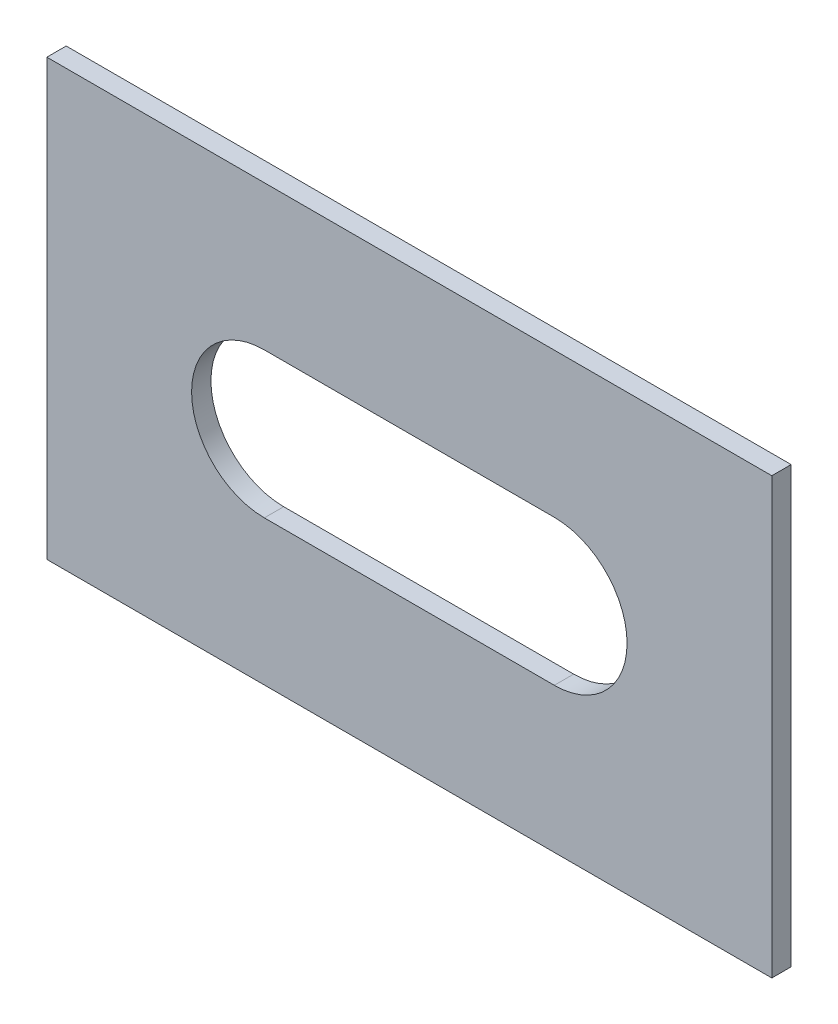
SolidWorks part; units mm, degrees
ref_plane "Front" through (0, 0, 0) normal (0, 0, 1) x (1, 0, 0)
ref_plane "Top" through (0, 0, 0) normal (0, 1, 0) x (1, 0, 0)
ref_plane "Right" through (0, 0, 0) normal (1, 0, 0) x (0, 0, -1)
sketch "Sketch1" plane through (0, 0, 0) normal (0, 0, 1) x (1, 0, 0)
  line L0 (29.95, 29.95) -> (45, 29.95) construction
  line L1 (0, 0) -> (150, 0)
  line L2 (0, 0) -> (0, 90)
  line L3 (0, 90) -> (150, 90)
  line L4 (150, 0) -> (150, 90)
  line L5 (45, 29.95) -> (105, 29.95)
  line L6 (45, 60.05) -> (105, 60.05)
  line L7 (29.95, 29.95) -> (29.95, 45) construction
  arc A6 (45, 60.05) -> (45, 29.95) centre (45, 45) ccw
  arc A7 (105, 29.95) -> (105, 60.05) centre (105, 45) ccw
  point P14 (120.05, 45)
  dimension "D3" = 30.1
  dimension "D4" = 90.1
  dimension "D1" = 150
  dimension "D2" = 90
  dimension "D5" = 45
  dimension "D6" = 45
extrude "Boss-Extrude1" add sketch "Sketch1" along normal blind 4
